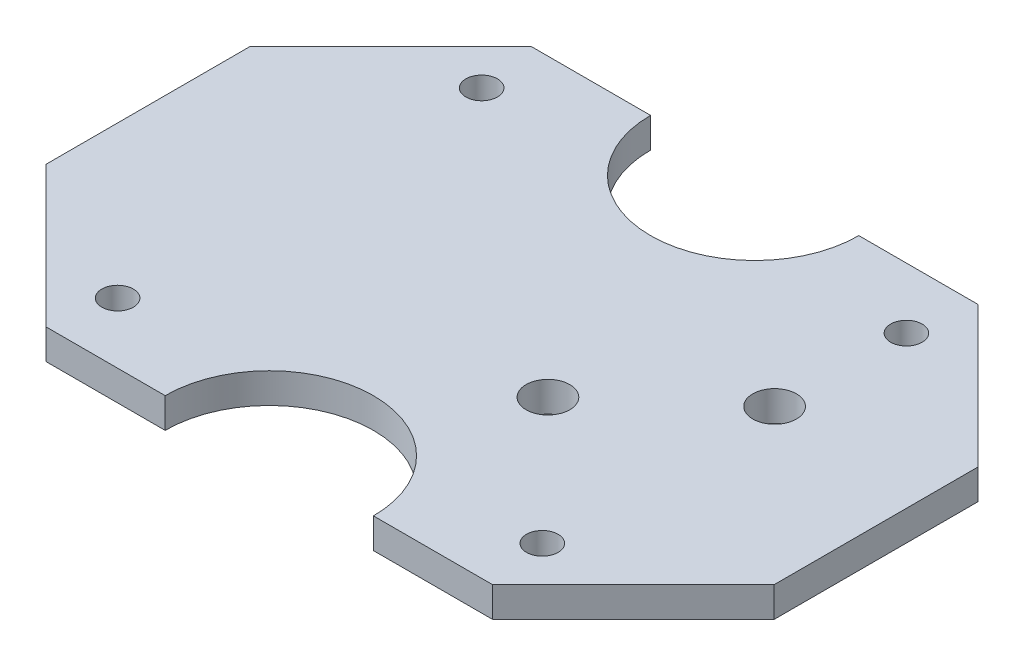
SolidWorks part; units mm, degrees
material "Acrylic (Medium-high impact)"
ref_plane "Front Plane" through (0, 0, 0) normal (0, 0, 1) x (1, 0, 0)
ref_plane "Top Plane" through (0, 0, 0) normal (0, 1, 0) x (1, 0, 0)
ref_plane "Right Plane" through (0, 0, 0) normal (1, 0, 0) x (0, 0, -1)
sketch "Sketch1" plane through (0, 0, 0) normal (0, 1, 0) x (1, 0, 0)
  line L0 (23.368, -25.4) -> (38.1, -10.668)
  line L1 (-23.368, 25.4) -> (-10.8997, 25.4)
  line L2 (-38.1, 10.668) -> (-38.1, -10.668)
  line L3 (-23.368, -25.4) -> (-10.8997, -25.4)
  line L4 (38.1, 10.668) -> (38.1, -10.668)
  line L5 (-52.832, 25.4) -> (23.368, -25.4) construction
  line L6 (-52.832, -25.4) -> (23.368, 25.4) construction
  line L7 (-2.54, -10.668) -> (41.529, -10.668) construction
  line L8 (0, -25.4) -> (0, 25.4) construction
  line L9 (-38.1, 0) -> (38.1, 0) construction
  line L10 (-23.368, -25.4) -> (-38.1, -10.668)
  line L11 (23.368, 25.4) -> (38.1, 10.668)
  line L12 (-23.368, 25.4) -> (-38.1, 10.668)
  line L13 (10.8997, -25.4) -> (23.368, -25.4)
  line L14 (10.8997, 25.4) -> (23.368, 25.4)
  circle A0 centre (-22.225, 19.05) radius 1.651
  circle A1 centre (22.225, 19.05) radius 1.651
  circle A2 centre (22.225, -19.05) radius 1.651
  circle A3 centre (-22.225, -19.05) radius 1.651
  arc A4 (-10.8997, -25.4) -> (10.8997, -25.4) centre (0, -25.4) cw
  circle A5 centre (9.271, -5.5118) radius 2.286
  circle A6 centre (21.971, 5.5118) radius 2.286
  arc A7 (10.8997, 25.4) -> (-10.8997, 25.4) centre (0, 25.4) cw
  point P0 (-14.732, 0)
  dimension "D1" = 50.8
  dimension "D2" = 76.2
  dimension "D3" = 45
  dimension "D4" = 14.732
extrude "Boss-Extrude1" add sketch "Sketch1" along normal blind 3.1496
